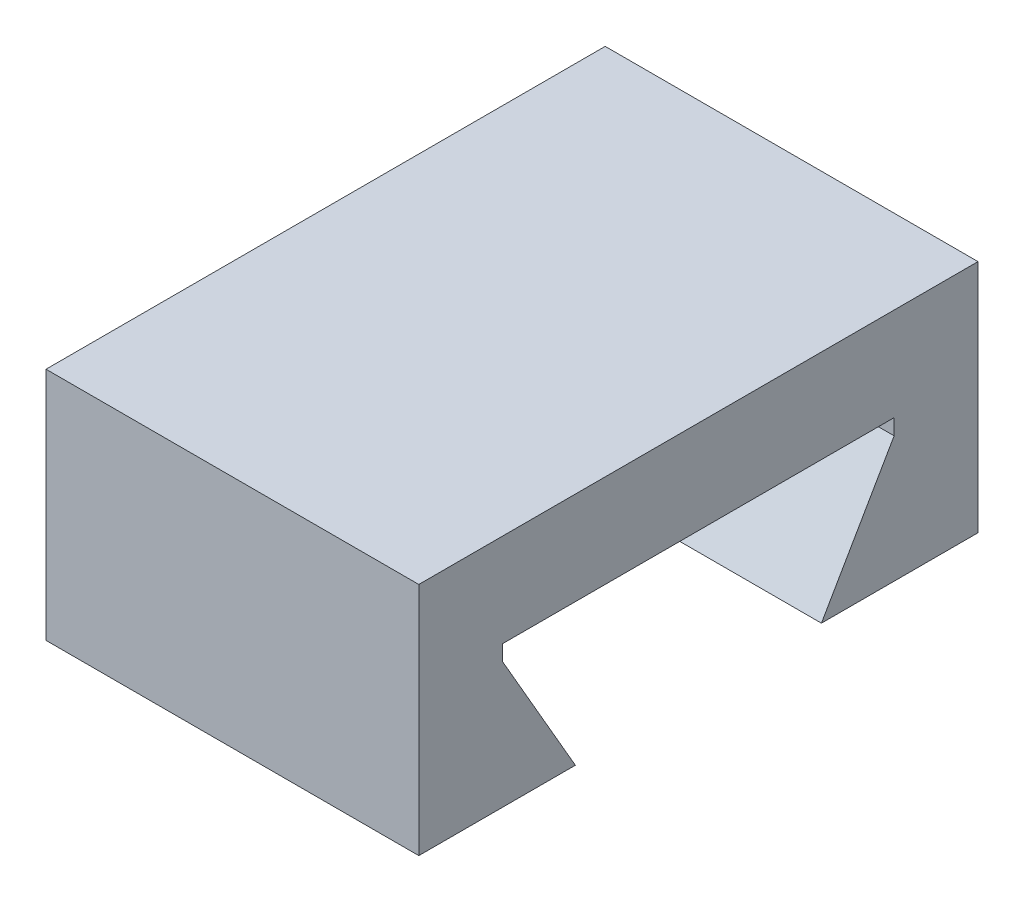
SolidWorks part; units mm, degrees
ref_plane "Front Plane" through (0, 0, 0) normal (0, 0, 1) x (1, 0, 0)
ref_plane "Top Plane" through (0, 0, 0) normal (0, 1, 0) x (1, 0, 0)
ref_plane "Right Plane" through (0, 0, 0) normal (1, 0, 0) x (0, 0, -1)
sketch "Sketch1" plane through (0, 0, 0) normal (1, 0, 0) x (0, 0, -1)
  line L0 (0, 0) -> (0, -16.002)
  line L1 (0, -16.002) -> (10.668, -16.002)
  line L2 (10.668, -16.002) -> (5.715, -7.4232)
  line L3 (5.715, -7.4232) -> (5.715, -6.35)
  line L4 (5.715, -6.35) -> (32.385, -6.35)
  line L5 (32.385, -6.35) -> (32.385, -7.4232)
  line L6 (32.385, -7.4232) -> (27.432, -16.002)
  line L7 (27.432, -16.002) -> (38.1, -16.002)
  line L8 (38.1, -16.002) -> (38.1, 0)
  line L9 (38.1, 0) -> (0, 0)
  dimension "D1" = 60
  dimension "D2" = 60
  dimension "D3" = 26.67
  dimension "D4" = 38.1
  dimension "D5" = 16.764
  dimension "D6" = 9.652
  dimension "D7" = 6.35
extrude "Boss-Extrude1" add sketch "Sketch1" along normal blind 25.4
